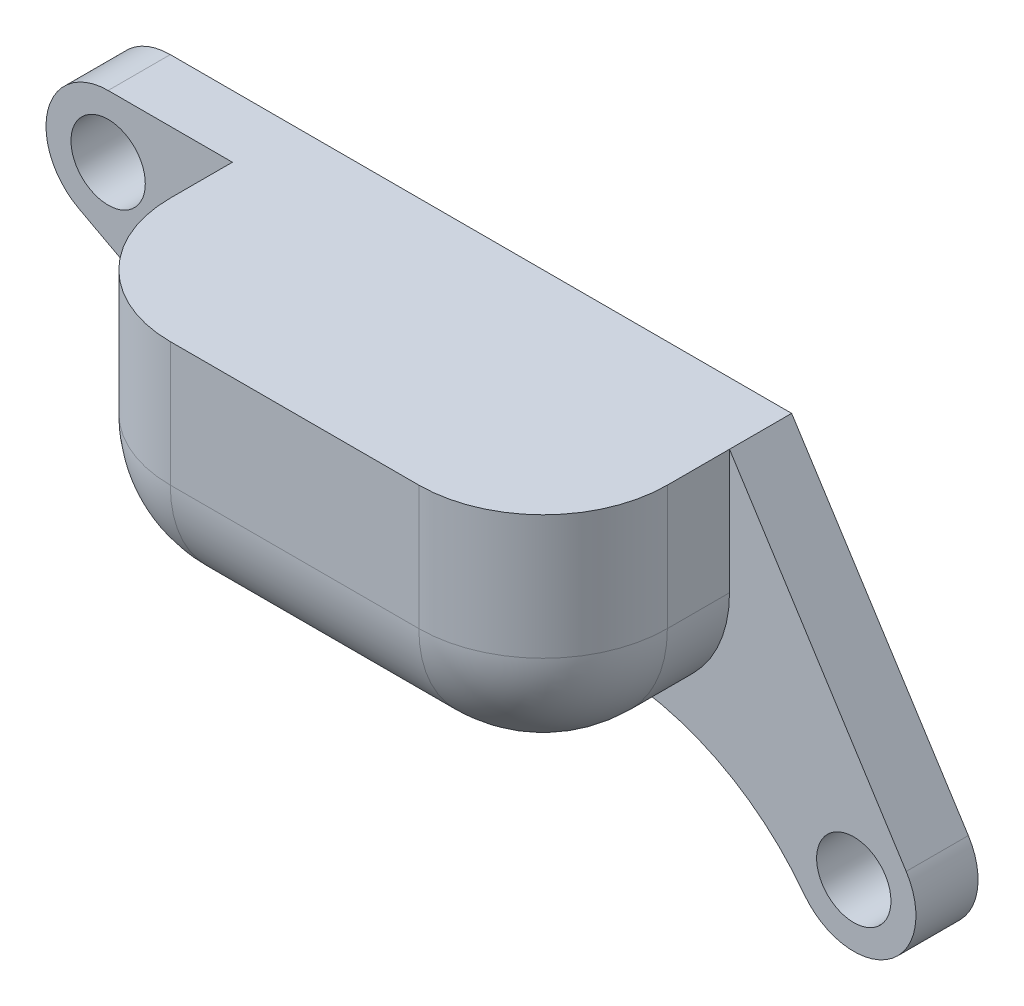
SolidWorks part; units mm, degrees
ref_plane "Front Plane" through (0, 0, 0) normal (0, 0, 1) x (1, 0, 0)
ref_plane "Top Plane" through (0, 0, 0) normal (0, 1, 0) x (1, 0, 0)
ref_plane "Right Plane" through (0, 0, 0) normal (1, 0, 0) x (0, 0, -1)
sketch "Sketch1" plane through (0, 0, 0) normal (0, 0, 1) x (1, 0, 0)
  line L0 (-12.7, 0) -> (12.7, 0)
  line L1 (-12.7, 0) -> (-12.7, -6.35)
  line L2 (-6.35, -12.7) -> (6.35, -12.7)
  line L3 (12.7, -6.35) -> (12.7, 0)
  arc A0 (6.35, -12.7) -> (12.7, -6.35) centre (6.35, -6.35) ccw
  arc A1 (-12.7, -6.35) -> (-6.35, -12.7) centre (-6.35, -6.35) ccw
  point P4 (0, 0)
  point P11 (-12.7, -12.7)
  dimension "D3" = 6.35
  dimension "D1" = 25.4
  dimension "D2" = 12.7
extrude "Boss-Extrude1" add sketch "Sketch1" along normal blind 12.7
sketch "Sketch2" plane through (0, 0, 0) normal (0, 0, -1) x (-1, 0, 0)
  line L0 (12.7, 0) -> (12.7, -6.35) construction
  line L1 (12.7, 0) -> (12.7, -6.35)
  line L2 (12.7, 0) -> (19.05, 0)
  line L3 (9.3382, -11.9529) -> (20.5441, -5.9765)
  line L4 (-12.7, 0) -> (-21.7277, -14.1689)
  line L5 (-12.7, -6.35) -> (-12.7, 0) construction
  line L6 (-12.7, -6.35) -> (-12.7, 0)
  arc A0 (6.35, -12.7) -> (12.7, -6.35) centre (6.35, -6.35) ccw construction
  arc A1 (9.3382, -11.9529) -> (12.7, -6.35) centre (6.35, -6.35) ccw
  arc A2 (19.05, 0) -> (20.5441, -5.9765) centre (19.05, -3.175) cw
  arc A3 (-21.7277, -14.1689) -> (-16.51, -17.78) centre (-19.05, -15.875) ccw
  arc A4 (-6.35, -12.7) -> (-16.51, -17.78) centre (-6.35, -25.4) ccw
  arc A5 (-12.7, -6.35) -> (-6.35, -12.7) centre (-6.35, -6.35) ccw construction
  arc A6 (-12.7, -6.35) -> (-6.35, -12.7) centre (-6.35, -6.35) ccw
  dimension "D1" = 19.05
  dimension "D3" = 3.175
  dimension "D4" = 15.875
  dimension "D2" = 3.175
  dimension "D5" = 19.05
extrude "Boss-Extrude2" add sketch "Sketch2" against normal blind 3.175
fillet "Fillet1" radius 6.35 5 edges at (12.7, -3.175, 12.7) (10.8401, -10.8401, 12.7) (0, -12.7, 12.7) (-10.8401, -10.8401, 12.7) (-12.7, -3.175, 12.7)
hole_wizard "#6 Clearance Hole1" positions "Sketch3" profile "Sketch4" hole size "#6" standard "ANSI Inch" end condition through all
sketch "Sketch3" plane through (0, 0, 3.175) normal (0, 0, 1) x (1, 0, 0)
  point P0 (-19.05, -3.175)
  point P3 (19.05, -15.875)
sketch "Sketch4" plane through (-19.05, -3.175, 3.175) normal (1, 0, 0) x (0, -1, 0)
  line L0 (0, 0) -> (0, 3.175)
  line L1 (0, 3.175) -> (1.8986, 3.175)
  line L2 (1.8986, 3.175) -> (1.8986, 0)
  line L5 (1.8986, 0) -> (0, 0)
  line L11 (0, -6.35) -> (0, 107.95) construction
  dimension "Thru Hole Dia." = 3.7973
  dimension "Thru Hole Depth" = 3.175
